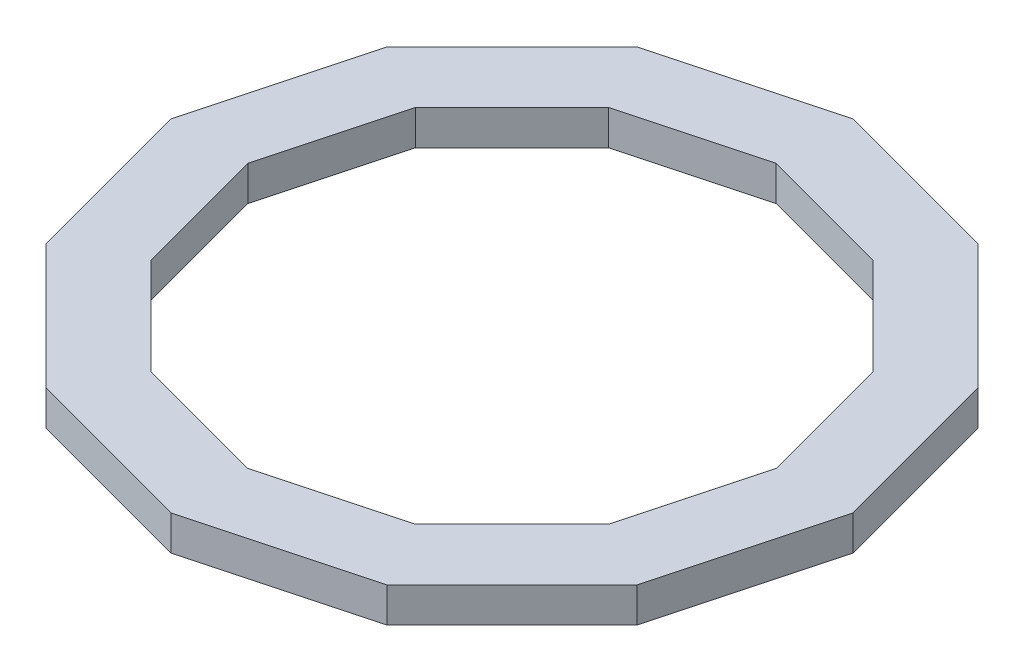
SolidWorks part; units mm, degrees
ref_plane "Front Plane" through (0, 0, 0) normal (0, 0, 1) x (1, 0, 0)
ref_plane "Top Plane" through (0, 0, 0) normal (0, 1, 0) x (1, 0, 0)
ref_plane "Right Plane" through (0, 0, 0) normal (1, 0, 0) x (0, 0, -1)
sketch "Sketch2" plane through (0, 0, 0) normal (0, 1, 0) x (1, 0, 0)
  line L0 (0, 0) -> (-144.3887, 0) construction
  line L1 (186.4623, 0) -> (161.4811, 93.2312)
  line L2 (161.4811, 93.2312) -> (93.2312, 161.4811)
  line L3 (93.2312, 161.4811) -> (0, 186.4623)
  line L4 (0, 186.4623) -> (-93.2312, 161.4811)
  line L5 (-93.2312, 161.4811) -> (-161.4811, 93.2312)
  line L6 (-161.4811, 93.2312) -> (-186.4623, 0)
  line L7 (-186.4623, 0) -> (-161.4811, -93.2312)
  line L8 (-161.4811, -93.2312) -> (-93.2312, -161.4811)
  line L9 (-93.2312, -161.4811) -> (0, -186.4623)
  line L10 (0, -186.4623) -> (93.2312, -161.4811)
  line L11 (93.2312, -161.4811) -> (161.4811, -93.2312)
  line L12 (161.4811, -93.2312) -> (186.4623, 0)
  line L13 (144.3887, 0) -> (125.0443, 72.1943)
  line L14 (125.0443, 72.1943) -> (72.1943, 125.0443)
  line L15 (72.1943, 125.0443) -> (0, 144.3887)
  line L16 (0, 144.3887) -> (-72.1943, 125.0443)
  line L17 (-72.1943, 125.0443) -> (-125.0443, 72.1943)
  line L18 (-125.0443, 72.1943) -> (-144.3887, 0)
  line L19 (-144.3887, 0) -> (-125.0443, -72.1943)
  line L20 (-125.0443, -72.1943) -> (-72.1943, -125.0443)
  line L21 (-72.1943, -125.0443) -> (0, -144.3887)
  line L22 (0, -144.3887) -> (72.1943, -125.0443)
  line L23 (72.1943, -125.0443) -> (125.0443, -72.1943)
  line L24 (125.0443, -72.1943) -> (144.3887, 0)
  circle A0 centre (0, 0) radius 180.1088 construction
  circle A1 centre (0, 0) radius 139.4688 construction
  dimension "D1" = 96.52
  dimension "D2" = 40.64
extrude "Boss-Extrude2" add sketch "Sketch2" along normal blind 19.05
